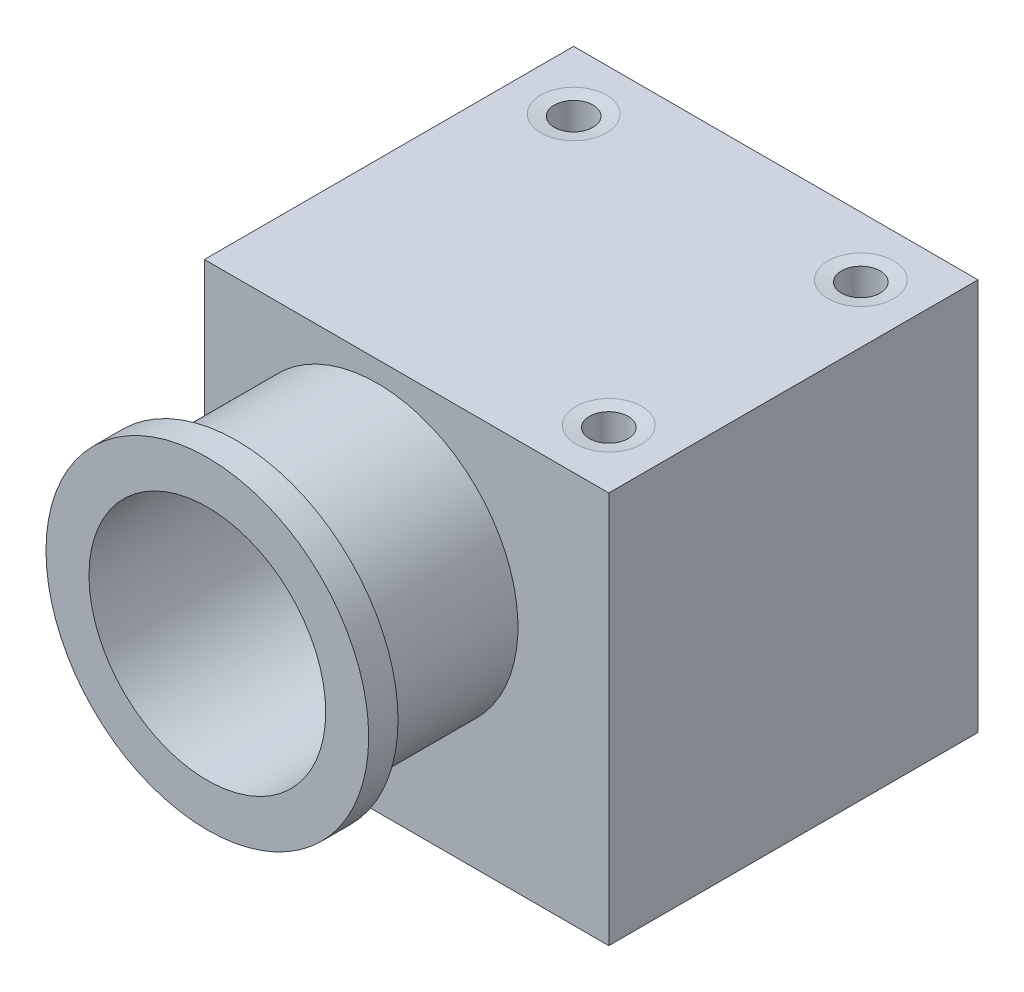
SolidWorks part; units mm, degrees
material "PTFE (general)"
ref_plane "Front Plane" through (0, 0, 0) normal (0, 0, 1) x (1, 0, 0)
ref_plane "Top Plane" through (0, 0, 0) normal (0, 1, 0) x (1, 0, 0)
ref_plane "Right Plane" through (0, 0, 0) normal (1, 0, 0) x (0, 0, -1)
sketch "Sketch1" plane through (0, 0, 0) normal (0, 0, 1) x (1, 0, 0)
  line L1 (-7.493, -8.4963) -> (7.493, -8.4963)
  line L2 (-7.493, -8.4963) -> (-7.493, 8.4963)
  line L3 (-7.493, 8.4963) -> (7.493, 8.4963)
  line L4 (7.493, -8.4963) -> (7.493, 8.4963)
  line L5 (-7.493, -8.4963) -> (7.493, 8.4963) construction
  line L6 (-7.493, 8.4963) -> (7.493, -8.4963) construction
  point P0 (0, 0)
  dimension "D1" = 14.986
  dimension "D2" = 16.9926
extrude "Boss-Extrude4" add sketch "Sketch1" against normal blind 24.1554 contours L3 L4 L1 L2
sketch "Sketch10" plane through (0, 0, 0) normal (0, 0, 1) x (1, 0, 0)
  circle A0 centre (0, 1.5037) radius 1.4224
  dimension "D1" = 2.8448
extrude "Cut-Extrude6" cut sketch "Sketch10" against normal blind 24.1554
sketch "Sketch11" plane through (0, 0, 0) normal (0, 0, 1) x (1, 0, 0)
  circle A0 centre (0, 1.5037) radius 3.2639
  dimension "D1" = 6.5278
extrude "Cut-Extrude7" cut sketch "Sketch11" against normal blind 19.558
sketch "Sketch12" plane through (0, 0, 0) normal (0, 0, 1) x (1, 0, 0)
  circle A0 centre (0, 1.5037) radius 5.1308
  dimension "D1" = 10.2616
extrude "Cut-Extrude8" cut sketch "Sketch12" against normal blind 18.288
sketch "Sketch13" plane through (0, 0, 0) normal (0, 0, 1) x (1, 0, 0)
  line L1 (-7.493, 8.4963) -> (7.493, 8.4963)
  line L2 (-7.493, 8.4963) -> (-7.493, -8.4963)
  line L3 (-7.493, -8.4963) -> (7.493, -8.4963)
  line L4 (7.493, 8.4963) -> (7.493, -8.4963)
  circle A0 centre (0, 1.5037) radius 5.1308
extrude "Cut-Extrude9" cut sketch "Sketch13" against normal blind 7.366
sketch "Sketch14" plane through (0, 0, -7.366) normal (0, 0, 1) x (1, 0, 0)
  circle A0 centre (0, 1.5037) radius 5.1308
  circle A1 centre (0, 1.5037) radius 6.096
  dimension "D1" = 12.192
extrude "Boss-Extrude5" add sketch "Sketch14" along normal blind 6.096
sketch "Sketch15" plane through (0, 0, -1.27) normal (0, 0, 1) x (1, 0, 0)
  circle A0 centre (0, 1.5037) radius 5.1308
  circle A1 centre (0, 1.5037) radius 6.9926
extrude "Boss-Extrude6" add sketch "Sketch15" along normal blind 1.27
sketch "Sketch16" plane through (0, 0, -24.1554) normal (0, 0, -1) x (-1, 0, 0)
  line L1 (7.493, -8.4963) -> (-7.493, -8.4963)
  line L2 (7.493, -8.4963) -> (7.493, 8.4963)
  line L3 (7.493, 8.4963) -> (-7.493, 8.4963)
  line L4 (-7.493, -8.4963) -> (-7.493, 8.4963)
extrude "Cut-Extrude10" cut sketch "Sketch16" against normal blind 0.7874
sketch "Sketch18" plane through (7.493, 0, 0) normal (1, 0, 0) x (0, 0, -1)
  line L1 (7.366, 8.4963) -> (23.368, 8.4963)
  line L2 (7.366, 8.4963) -> (7.366, -8.4963)
  line L3 (7.366, -8.4963) -> (23.368, -8.4963)
  line L4 (23.368, 8.4963) -> (23.368, -8.4963)
extrude "Boss-Extrude7" add sketch "Sketch18" along normal blind 2.54
sketch "Sketch19" plane through (0, 8.4963, 0) normal (0, 1, 0) x (1, 0, 0)
  line L0 (10.033, 7.366) -> (-7.493, 7.366) construction
  line L1 (10.033, 23.368) -> (10.033, 7.366) construction
  line L2 (-7.493, 23.368) -> (10.033, 23.368) construction
  line L3 (-7.493, 23.368) -> (-7.493, 7.366) construction
  circle A0 centre (-4.953, 20.828) radius 0.8382
  circle A1 centre (7.493, 20.828) radius 0.8382
  circle A2 centre (7.493, 9.906) radius 0.8382
  dimension "D1" = 1.6764
  dimension "D2" = 1.6764
  dimension "D3" = 1.6764
  dimension "D4" = 2.54
  dimension "D5" = 2.54
  dimension "D6" = 2.54
  dimension "D7" = 2.54
  dimension "D8" = 2.54
  dimension "D9" = 2.54
extrude "Cut-Extrude11" cut sketch "Sketch19" against normal blind 20.32
ref_plane "Plane2" through (0, 7.6073, 0) normal (0, 1, 0) x (1, 0, 0)
sketch "Sketch22" plane through (0, 8.4963, 0) normal (0, 1, 0) x (1, 0, 0)
  circle A0 centre (-4.953, 20.828) radius 1.4224
  circle A1 centre (7.493, 20.828) radius 1.4224
  circle A2 centre (7.493, 9.906) radius 1.4224
  dimension "D1" = 2.8448
  dimension "D2" = 2.8448
  dimension "D3" = 2.8448
extrude "Cut-Extrude13" cut sketch "Sketch22" against normal blind 0.889 draft 82
sketch "Sketch23" plane through (-7.493, 0, 0) normal (-1, 0, 0) x (0, 0, 1)
sketch "Sketch24" plane through (0, -8.4963, 0) normal (0, -1, 0) x (1, 0, 0)
  line L0 (0, -18.288) -> (0, 0) construction
  line L1 (-6.5913, -18.2626) -> (6.5913, -18.2626)
  line L2 (-6.5913, -18.2626) -> (-6.5913, -17.4752)
  line L3 (-6.5913, -17.4752) -> (6.5913, -17.4752)
  line L4 (6.5913, -18.2626) -> (6.5913, -17.4752)
  line L5 (-6.5913, -18.2626) -> (6.5913, -17.4752) construction
  line L6 (-6.5913, -17.4752) -> (6.5913, -18.2626) construction
  line L7 (-7.493, -7.366) -> (10.033, -7.366) construction
  point P0 (0, -17.8689)
  dimension "D1" = 0.7874
  dimension "D2" = 13.1826
  dimension "D3" = 10.1092
extrude "Cut-Extrude14" cut sketch "Sketch24" against normal blind 16.256
